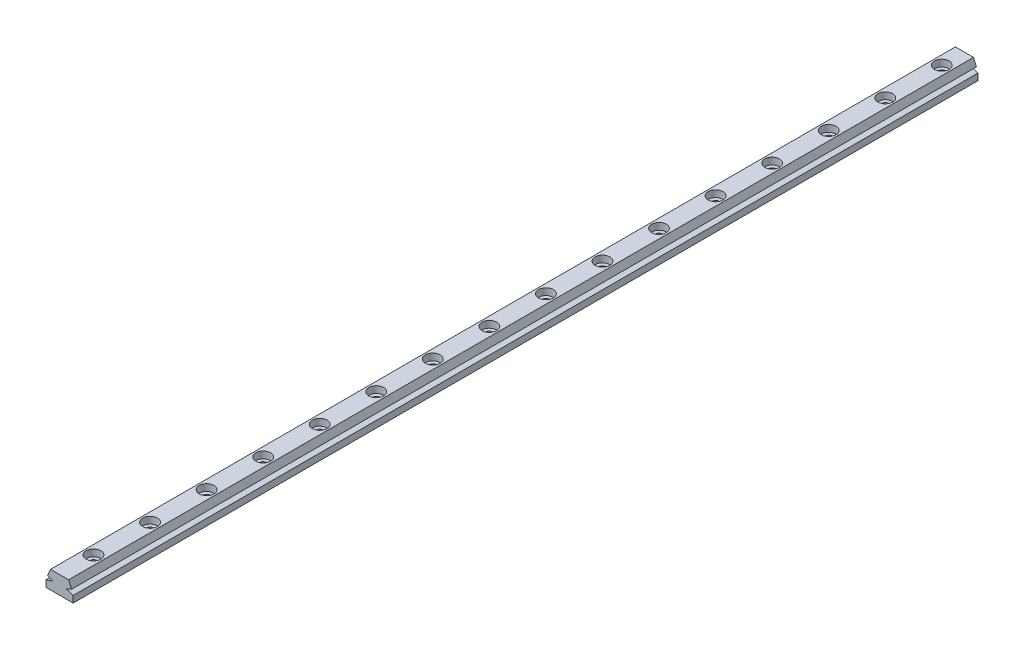
SolidWorks part; units mm, degrees
ref_plane "前视基准面" through (0, 0, 0) normal (0, 0, 1) x (1, 0, 0)
ref_plane "上视基准面" through (0, 0, 0) normal (0, 1, 0) x (1, 0, 0)
ref_plane "右视基准面" through (0, 0, 0) normal (1, 0, 0) x (0, 0, -1)
ref_plane "基准面4" through (0, 0, 0) normal (0, 0, -1) x (-1, 0, 0)
sketch "草图1" plane through (0, 0, 0) normal (0, 0, -1) x (-1, 0, 0)
  line L0 (-4, 4.9582) -> (-5.3, 1.9582)
  line L1 (-6, -2.9749) -> (-6, -0.0418)
  line L5 (-6, -2.9749) -> (6, -2.9749)
  line L6 (6, -2.9749) -> (6, -0.0418)
  line L9 (4, 4.9582) -> (-4, 4.9582)
  line L12 (4, 4.9582) -> (5.3, 1.9582)
  line L13 (5.3, 1.9582) -> (3, 0.9582)
  line L16 (-5.3, 1.9582) -> (-3, 0.9582)
  line L17 (3, 0.9582) -> (6, -0.0418)
  line L18 (-3, 0.9582) -> (-6, -0.0418)
extrude "凸台-拉伸1" add sketch "草图1" against normal blind 400
hole_wizard "M3 六角头机械螺钉的柱形沉头孔1" positions "草图3" profile "草图2" counterbore size "M3" standard "ANSI Metric"
sketch "草图3" plane through (0, 4.9582, 0) normal (0, 1, 0) x (1, 0, 0)
  point P0 (0, -385)
  point P1 (0, -360)
  point P2 (0, -335)
  point P3 (0, -310)
  point P4 (0, -285)
  point P5 (0, -260)
  point P6 (0, -235)
  point P7 (0, -210)
  point P8 (0, -185)
  point P9 (0, -160)
  point P10 (0, -135)
  point P11 (0, -110)
  point P12 (0, -85)
  point P13 (0, -60)
  point P14 (0, -10)
  point P15 (0, -35)
sketch "草图2" plane through (0, 4.9582, 385) normal (1, 0, 0) x (0, 0, 1)
  line L0 (0, 0) -> (0, 7.9331)
  line L1 (0, 7.9331) -> (1.7, 7.9331)
  line L3 (1.7, 7.9331) -> (1.7, 3)
  line L4 (1.7, 3) -> (3.25, 3)
  line L5 (3.25, 3) -> (3.25, 0)
  line L7 (3.25, 0) -> (0, 0)
  line L11 (0, -6.35) -> (0, 107.95) construction
  dimension "通孔孔直径" = 3.4
  dimension "通孔孔深度" = 7.9331
  dimension "柱形沉头孔直径" = 6.5
  dimension "柱形沉头孔深度" = 3
